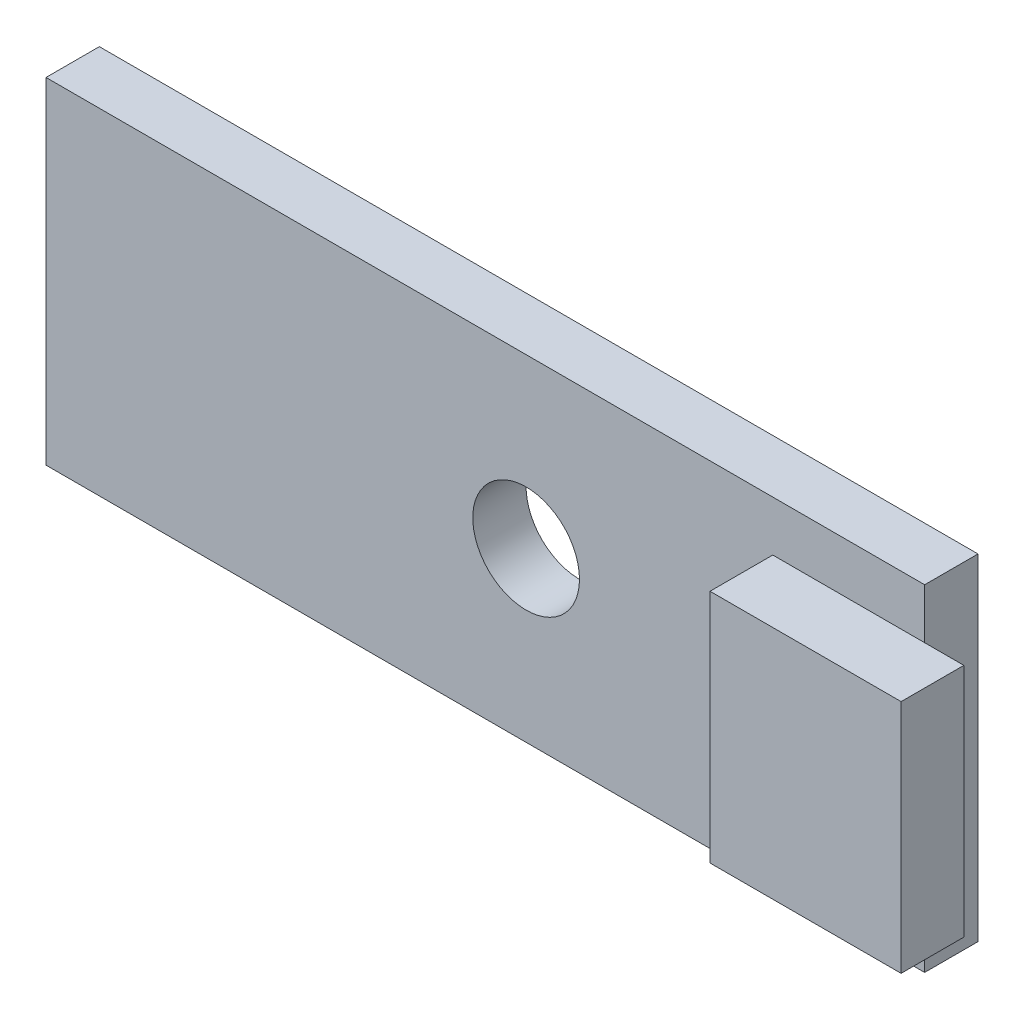
SolidWorks part; units mm, degrees
ref_plane "Front Plane" through (0, 0, 0) normal (0, 0, 1) x (1, 0, 0)
ref_plane "Top Plane" through (0, 0, 0) normal (0, 1, 0) x (1, 0, 0)
ref_plane "Right Plane" through (0, 0, 0) normal (1, 0, 0) x (0, 0, -1)
sketch "Sketch1" plane through (0, 0, 0) normal (0, 0, 1) x (1, 0, 0)
  line L1 (-14, -5.35) -> (14, -5.35)
  line L2 (-14, -5.35) -> (-14, 5.35)
  line L3 (-14, 5.35) -> (14, 5.35)
  line L4 (14, -5.35) -> (14, 5.35)
  line L5 (-14, -5.35) -> (14, 5.35) construction
  line L6 (-14, 5.35) -> (14, -5.35) construction
  point P0 (0, 0)
  dimension "D1" = 28
  dimension "D2" = 10.7
extrude "Boss-Extrude1" add sketch "Sketch1" along normal blind 1.7
sketch "Sketch2" plane through (0, 0, 1.7) normal (0, 0, 1) x (1, 0, 0)
  line L0 (14, -5.35) -> (14, 5.35) construction
  line L1 (14, 0) -> (-14, 0) construction
  line L2 (-14, 5.35) -> (-14, -5.35) construction
  circle A0 centre (1.3, 0) radius 1.7
  dimension "D1" = 3.4
  dimension "D2" = 12.7
extrude "Cut-Extrude1" cut sketch "Sketch2" against normal through all
sketch "Sketch3" plane through (0, 0, 1.7) normal (0, 0, 1) x (1, 0, 0)
  line L0 (55, 0) -> (-55, 0) construction
  line L1 (9.16, -3.75) -> (15.25, -3.75)
  line L2 (9.16, -3.75) -> (9.16, 3.75)
  line L3 (9.16, 3.75) -> (15.25, 3.75)
  line L4 (15.25, -3.75) -> (15.25, 3.75)
  line L5 (9.16, -3.75) -> (15.25, 3.75) construction
  line L6 (9.16, 3.75) -> (15.25, -3.75) construction
  line L7 (14, 0) -> (-0.4, 0) construction
  line L8 (14, -5.35) -> (14, 5.35) construction
  circle A0 centre (1.3, 0) radius 1.7 construction
  point P0 (12.205, 0)
  dimension "D1" = 6.09
  dimension "D2" = 7.5
  dimension "D3" = 1.25
extrude "Boss-Extrude2" add sketch "Sketch3" along normal blind 2
